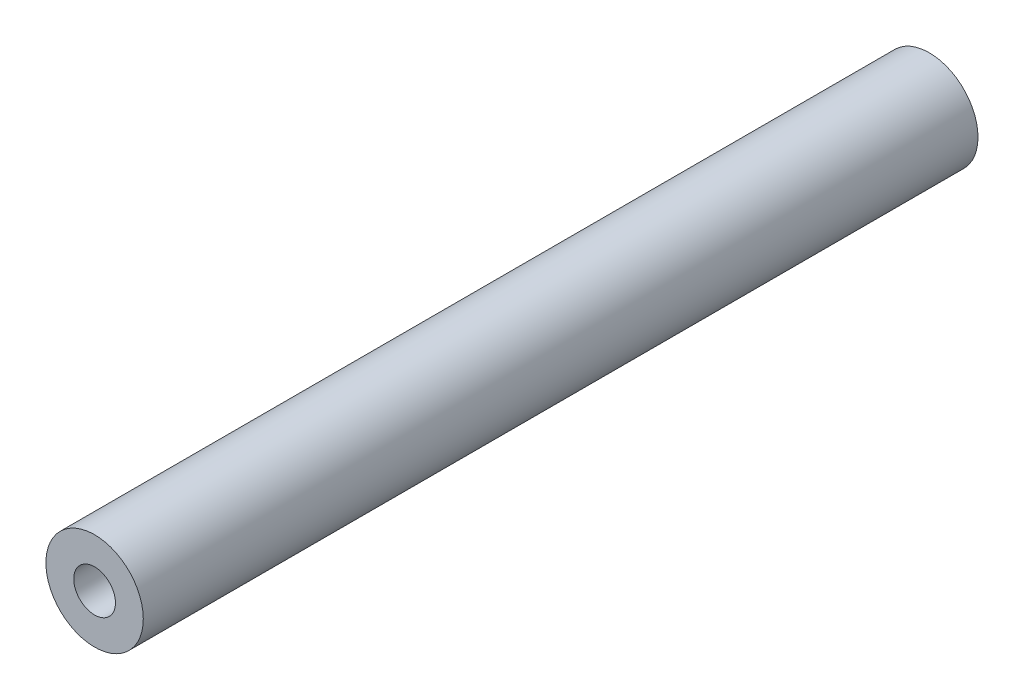
SolidWorks part; units mm, degrees
material "AISI 4140 Steel, quenched & tempered"
ref_plane "Front Plane" through (0, 0, 0) normal (1, 0, 0) x (0, 1, 0)
ref_plane "Top Plane" through (0, 0, 0) normal (0, 0, 1) x (0, 1, 0)
ref_plane "Right Plane" through (0, 0, 0) normal (0, 1, 0) x (-1, 0, 0)
sketch "Sketch1" plane through (0, 0, 0) normal (0, 0, 1) x (0, 1, 0)
  circle A0 centre (0, 0) radius 7
  circle A1 centre (0, 0) radius 3
  dimension "D1" = 14
  dimension "D2" = 6
extrude "Boss-Extrude1" add sketch "Sketch1" along normal mid plane 120 contours A0 A1
